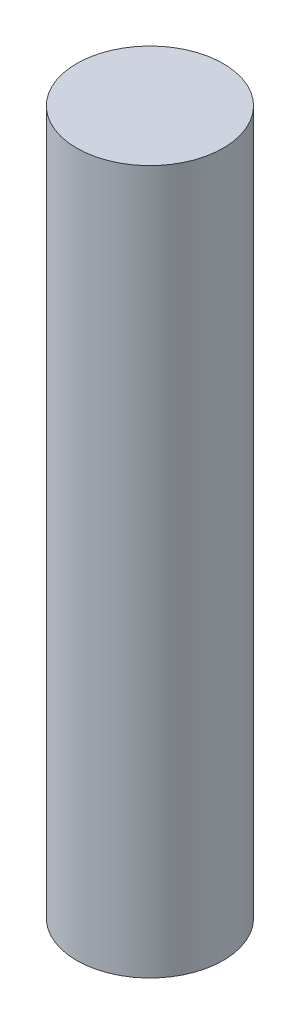
SolidWorks part; units mm, degrees
ref_plane "前视基准面" through (0, 0, 0) normal (0, 0, 1) x (1, 0, 0)
ref_plane "上视基准面" through (0, 0, 0) normal (0, 1, 0) x (1, 0, 0)
ref_plane "右视基准面" through (0, 0, 0) normal (1, 0, 0) x (0, 0, -1)
other "Configuration Table"
sketch "草图1" plane through (0, 0, 0) normal (0, 1, 0) x (1, 0, 0)
  circle A0 centre (0, 0) radius 2.5
  dimension "D1" = 5
extrude "凸台-拉伸1" add sketch "草图1" along normal blind 24
sketch "草图2" plane through (0, 24, 0) normal (0, 1, 0) x (1, 0, 0)
  circle A1 centre (0, 0) radius 2.5
  circle A2 centre (0, 0) radius 2.5
  dimension "D1" = 0
